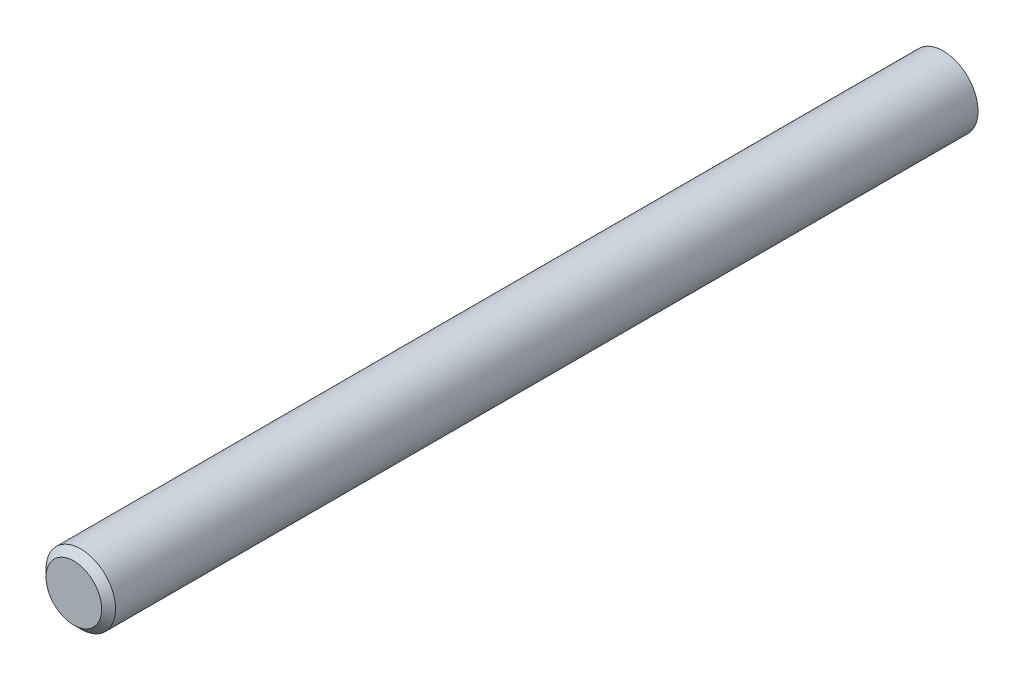
SolidWorks part; units mm, degrees
ref_plane "Front" through (0, 0, 0) normal (0, 0, 1) x (1, 0, 0)
ref_plane "Top" through (0, 0, 0) normal (0, 1, 0) x (1, 0, 0)
ref_plane "Right" through (0, 0, 0) normal (1, 0, 0) x (0, 0, -1)
sketch "Sketch1" plane through (0, 0, 0) normal (0, 0, 1) x (1, 0, 0)
  circle A0 centre (0, 0) radius 4
  dimension "dia" = 8
extrude "Extrude1" add sketch "Sketch1" along normal mid plane 600
sketch "Sketch2" plane through (0, 0, 0) normal (1, 0, 0) x (0, 0, -1)
  line L0 (300, 4) -> (-300, 4) construction
  point P0 (-300, 4)
  point P1 (300, 4)
  point P2 (-284, 4)
  point P5 (284, 4)
  dimension "D1" = 16
  dimension "D2" = 16
chamfer "Chamfer1" distance 0.8 angle 45 2 edges at (4, 0, -300) (4, 0, 300)
ref_plane "Plane1" through (0, 0, -300) normal (0, 0, -1) x (-1, 0, 0)
sketch "Sketch3" plane through (0, 0, -300) normal (0, 0, -1) x (-1, 0, 0)
  circle A0 centre (0, 0) radius 12.7568
extrude "Cut-Extrude1" cut sketch "Sketch3" against normal blind 500
equation "\"D1@Chamfer1\" = \"dia@Sketch1\" * .1"
equation "\"D1@Sketch2\"=\"dia@sketch1\"*2"
equation "\"D2@Sketch2\"=\"D1@Sketch2\""
